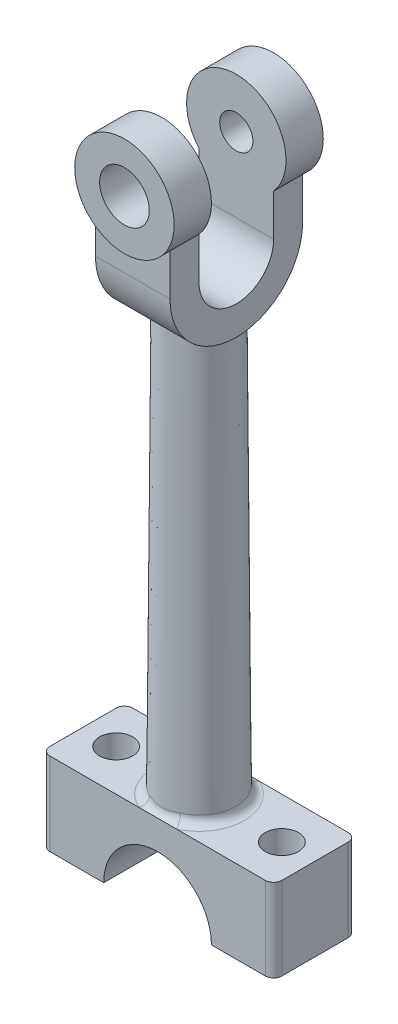
SolidWorks part; units mm, degrees
ref_plane "Front Plane" through (0, 0, 0) normal (0, 0, 1) x (1, 0, 0)
ref_plane "Top Plane" through (0, 0, 0) normal (0, 1, 0) x (1, 0, 0)
ref_plane "Right Plane" through (0, 0, 0) normal (1, 0, 0) x (0, 0, -1)
sketch "Sketch1" plane through (0, 0, 0) normal (0, 0, 1) x (1, 0, 0)
  line L0 (-14, 0) -> (14, 0)
  line L1 (-14, 10) -> (14, 10)
  line L2 (-14, 10) -> (-14, 0)
  line L4 (14, 10) -> (14, 0)
  point P0 (0, 0)
  point P9 (0, 10)
  dimension "D1" = 28
  dimension "D2" = 10
extrude "Boss-Extrude1" add sketch "Sketch1" along normal mid plane 10
sketch "Sketch2" plane through (0, 0, 0) normal (1, 0, 0) x (0, 0, -1)
  line L0 (0, 10) -> (0, 77)
  line L1 (-5, 10) -> (5, 10) construction
  line L2 (0, 77) -> (-4, 77)
  line L3 (-4, 77) -> (-4.5, 10)
  line L4 (-4.5, 10) -> (0, 10)
  line L5 (-5, 0) -> (5, 0) construction
  dimension "D1" = 4.5
  dimension "D2" = 4
  dimension "D3" = 77
revolve "Revolve2" add sketch "Sketch2" angle 360 about L0
sketch "Sketch6" plane through (0, 0, 0) normal (0, 0, 1) x (1, 0, 0)
  line L0 (4, 77) -> (-4, 77) construction
  circle A0 centre (0, 77) radius 6
  dimension "D1" = 12
extrude "Boss-Extrude3" add sketch "Sketch6" along normal mid plane 18
sketch "Sketch7" plane through (0, 0, 0) normal (1, 0, 0) x (0, 0, -1)
  line L0 (-8, 77) -> (8, 77)
  line L1 (8, 77) -> (8, 68)
  line L2 (-8, 77) -> (-8, 68)
  arc A1 (-8, 68) -> (8, 68) centre (0, 68) ccw
  point P0 (0, 0)
  dimension "D3" = 77
  dimension "D1" = 8
  dimension "D2" = 68
extrude "Boss-Extrude4" add sketch "Sketch7" along normal mid plane 9
sketch "Sketch8" plane through (0, 0, 9) normal (0, 0, 1) x (1, 0, 0)
  circle A0 centre (0, 77) radius 2
  circle A1 centre (0, 77) radius 6 construction
  dimension "D1" = 4
extrude "Cut-Extrude1" cut sketch "Sketch8" against normal through all both and the other way through all
sketch "Sketch9" plane through (0, 0, 0) normal (1, 0, 0) x (0, 0, -1)
  line L0 (0, 68) -> (0, 86.2688) construction
  line L1 (-4.5, 68) -> (-4.5, 86.2688)
  line L2 (4.5, 68) -> (4.5, 86.2688)
  arc A0 (-4.5, 68) -> (4.5, 68) centre (0, 68) ccw
  arc A1 (4.5, 86.2688) -> (-4.5, 86.2688) centre (0, 86.2688) ccw
  point P4 (0, 77.1344)
  dimension "D1" = 9
  dimension "D2" = 18.2688
extrude "Cut-Extrude2" cut sketch "Sketch9" against normal through all both and the other way through all
sketch "Sketch10" plane through (0, 0, 9) normal (0, 0, 1) x (1, 0, 0)
  circle A0 centre (0, 77) radius 3
  circle A1 centre (0, 77) radius 2 construction
  dimension "D1" = 6
extrude "Cut-Extrude3" cut sketch "Sketch10" against normal up to next and the other way through all
sketch "Sketch11" plane through (0, 10, 0) normal (0, 1, 0) x (1, 0, 0)
  line L1 (-14, -5) -> (-14, 5) construction
  line L2 (14, 5) -> (-14, 5) construction
  circle A0 centre (-10, 0) radius 2
  circle A1 centre (10, 0) radius 2
  dimension "D1" = 4
  dimension "D2" = 4
  dimension "D3" = 24
  dimension "D4" = 5
extrude "Cut-Extrude4" cut sketch "Sketch11" against normal up to next
fillet "Fillet1" radius 1 4 edges at (-14, 5, -5) (-14, 5, 5) (14, 5, -5) (14, 5, 5)
fillet "Fillet2" radius 1 1 edges at (0, 10, -4.5)
sketch "Sketch12" plane through (0, 0, 0) normal (0, 0, 1) x (1, 0, 0)
  line L0 (-13, 0) -> (13, 0) construction
  line L1 (-6.5, 0) -> (6.5, 0)
  arc A0 (-6.5, 0) -> (6.5, 0) centre (0, 0) cw
  dimension "D1" = 6.5
extrude "Cut-Extrude5" cut sketch "Sketch12" against normal through all both and the other way through all
